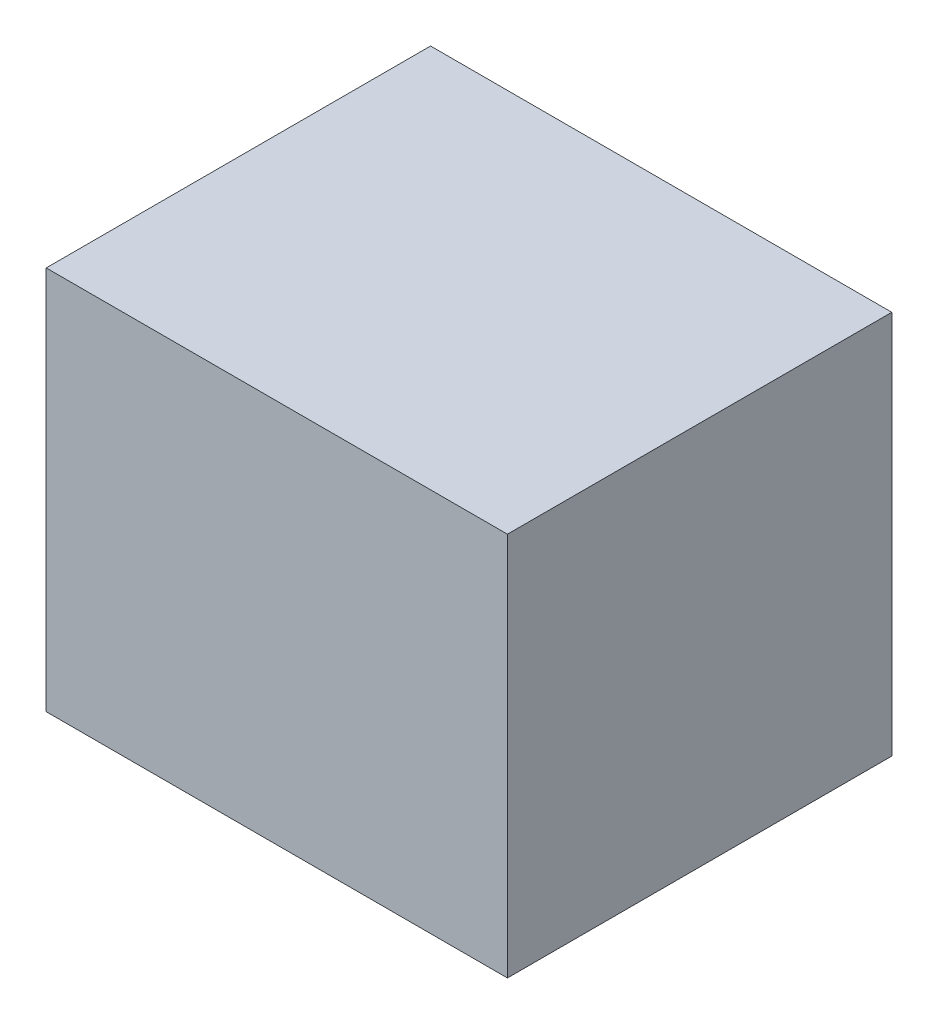
SolidWorks part; units mm, degrees
material "Gray Cast Iron"
ref_plane "Front Plane" through (0, 0, 0) normal (0, 0, 1) x (1, 0, 0)
ref_plane "Top Plane" through (0, 0, 0) normal (0, 1, 0) x (1, 0, 0)
ref_plane "Right Plane" through (0, 0, 0) normal (1, 0, 0) x (0, 0, -1)
sketch "Sketch1" plane through (0, 0, 0) normal (0, 0, 1) x (1, 0, 0)
  line L1 (0, 0) -> (600, 0)
  line L2 (0, 0) -> (0, 500)
  line L3 (0, 500) -> (600, 500)
  line L4 (600, 0) -> (600, 500)
  dimension "D1" = 600
  dimension "D2" = 500
extrude "Boss-Extrude1" add sketch "Sketch1" along normal blind 500
